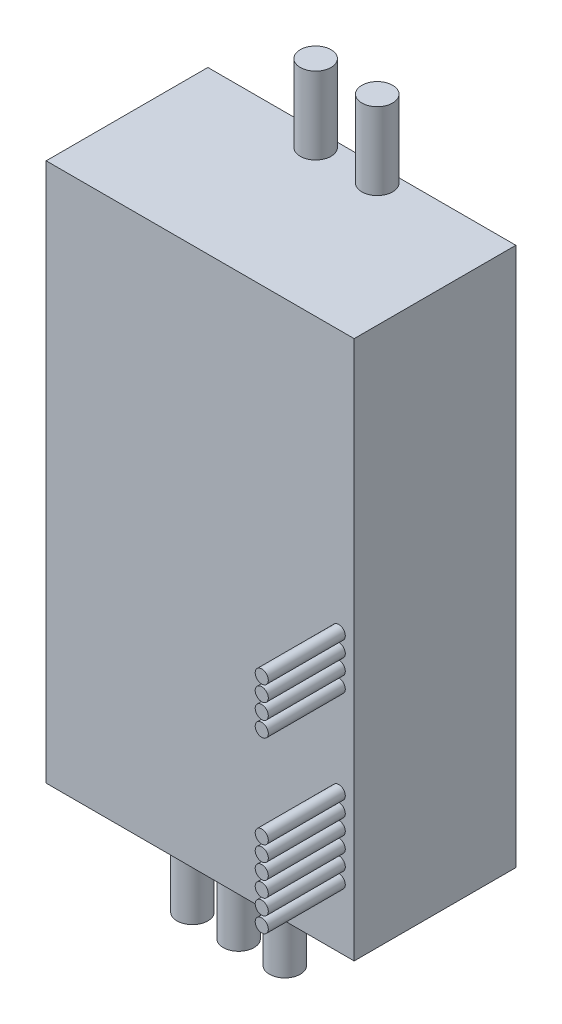
SolidWorks part; units mm, degrees
ref_plane "Front Plane" through (0, 0, 0) normal (1, 0, 0) x (0, 1, 0)
ref_plane "Top Plane" through (0, 0, 0) normal (0, 0, 1) x (0, 1, 0)
ref_plane "Right Plane" through (0, 0, 0) normal (0, 1, 0) x (-1, 0, 0)
sketch "Sketch1" plane through (0, 0, 0) normal (0, 0, 1) x (0, 1, 0)
  line L1 (-35, 20) -> (35, 20)
  line L2 (-35, 20) -> (-35, -20)
  line L3 (-35, -20) -> (35, -20)
  line L4 (35, 20) -> (35, -20)
  line L5 (-35, 20) -> (35, -20) construction
  line L6 (-35, -20) -> (35, 20) construction
  point P0 (0, 0)
  dimension "D1" = 70
  dimension "D2" = 40
extrude "Boss-Extrude1" add sketch "Sketch1" along normal blind 21
sketch "Sketch2" plane through (0, -35, 0) normal (0, -1, 0) x (1, 0, 0)
  line L0 (-20, 21) -> (20, 21) construction
  circle A0 centre (-6, 16) radius 2
  circle A1 centre (0, 16) radius 2
  circle A2 centre (6, 16) radius 2
  dimension "D1" = 4
  dimension "D2" = 5
  dimension "D3" = 6
  dimension "D4" = 6
extrude "Boss-Extrude2" add sketch "Sketch2" along normal blind 10
sketch "Sketch3" plane through (0, 35, 0) normal (0, 1, 0) x (-1, 0, 0)
  line L0 (-20, 0) -> (20, 0) construction
  circle A0 centre (-4, 2) radius 2
  circle A1 centre (4, 2) radius 2
  dimension "D1" = 4
  dimension "D2" = 4
  dimension "D3" = 4
extrude "Boss-Extrude3" add sketch "Sketch3" along normal blind 10
sketch "Sketch4" plane through (0, 0, 21) normal (0, 0, 1) x (1, 0, 0)
  line L0 (20, -35) -> (20, 35) construction
  line L1 (-20, -35) -> (20, -35) construction
  line L2 (18, -27) -> (18, -25) construction
  line L3 (18, -5) -> (18, -3) construction
  circle A0 centre (18, -27) radius 0.85
  circle A1 centre (18, -25) radius 0.85
  circle A2 centre (18, -23) radius 0.85
  circle A3 centre (18, -21) radius 0.85
  circle A4 centre (18, -19) radius 0.85
  circle A5 centre (18, -17) radius 0.85
  circle A6 centre (18, -5) radius 0.85
  circle A7 centre (18, -3) radius 0.85
  circle A8 centre (18, -1) radius 0.85
  circle A9 centre (18, 1) radius 0.85
  dimension "D1" = 1.7
  dimension "D2" = 2
  dimension "D3" = 8
  dimension "D5" = 2
  dimension "D6" = 12
  dimension "D8" = 2
  dimension "D4" = 6
  dimension "D7" = 4
extrude "Boss-Extrude4" add sketch "Sketch4" along normal blind 10
